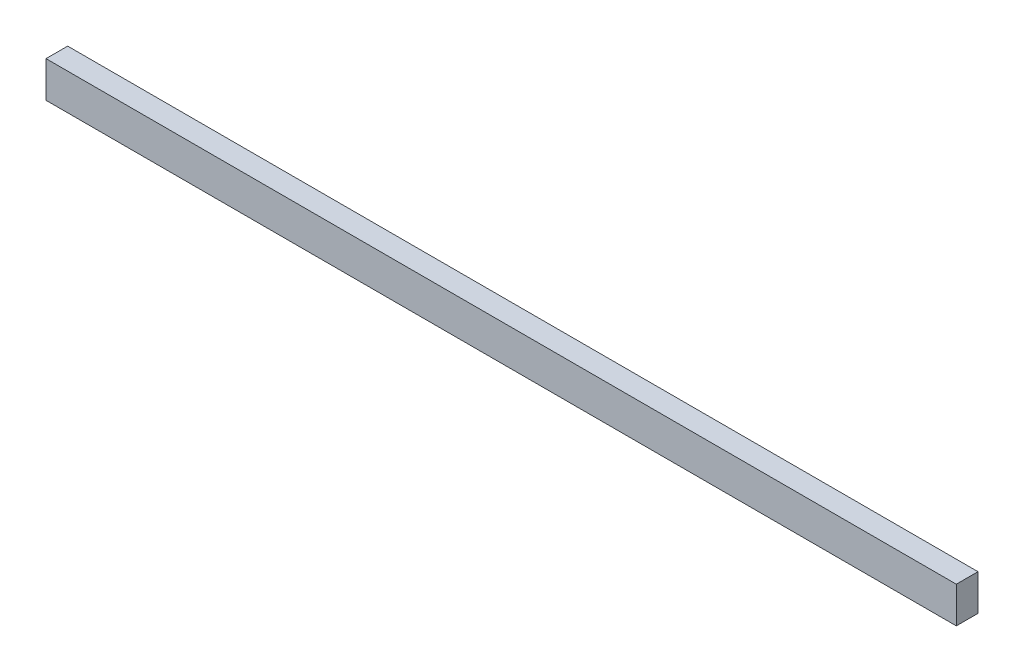
SolidWorks part; units mm, degrees
material "Pine"
ref_plane "Front Plane" through (0, 0, 0) normal (0, 0, 1) x (1, 0, 0)
ref_plane "Top Plane" through (0, 0, 0) normal (0, 1, 0) x (1, 0, 0)
ref_plane "Right Plane" through (0, 0, 0) normal (1, 0, 0) x (0, 0, -1)
sketch "Sketch1" plane through (0, 0, 0) normal (0, 1, 0) x (1, 0, 0)
  line L1 (-400.05, -9.525) -> (400.05, -9.525)
  line L2 (-400.05, -9.525) -> (-400.05, 9.525)
  line L3 (-400.05, 9.525) -> (400.05, 9.525)
  line L4 (400.05, -9.525) -> (400.05, 9.525)
  line L5 (-400.05, -9.525) -> (400.05, 9.525) construction
  line L6 (-400.05, 9.525) -> (400.05, -9.525) construction
  point P0 (0, 0)
  dimension "D1" = 19.05
  dimension "D2" = 800.1
extrude "Boss-Extrude1" add sketch "Sketch1" along normal blind 31.75
